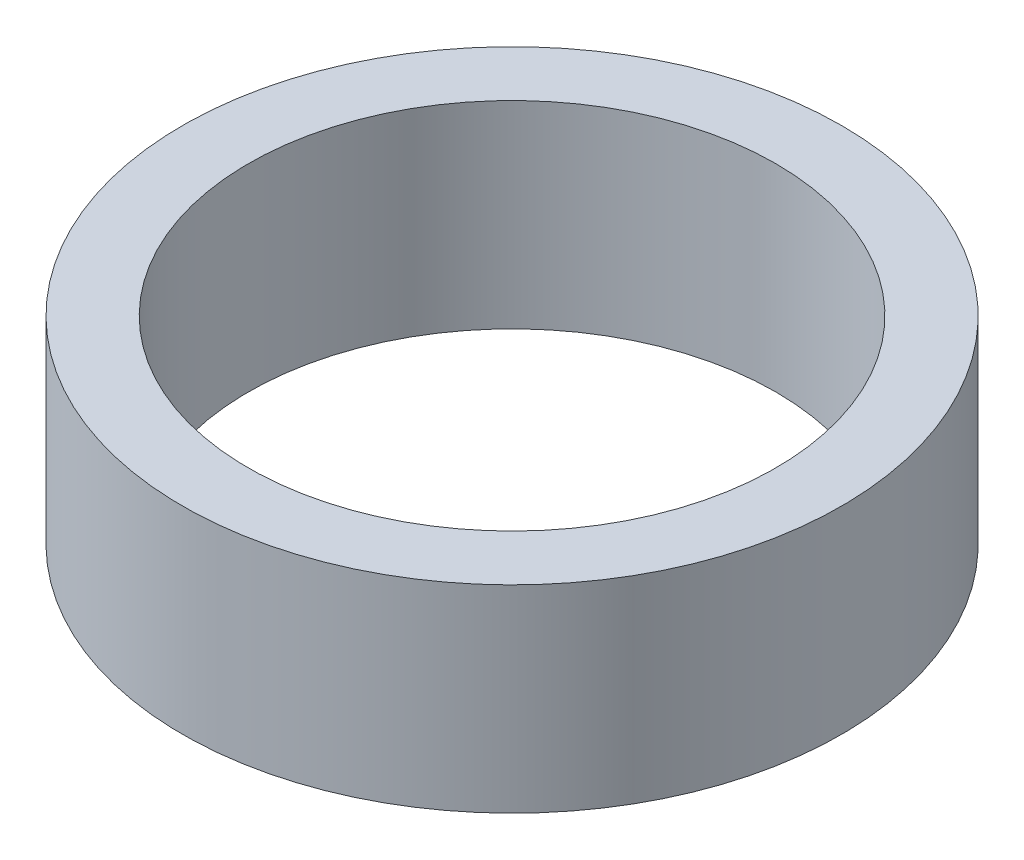
SolidWorks part; units mm, degrees
ref_plane "Front Plane" through (0, 0, 0) normal (0, 0, 1) x (1, 0, 0)
ref_plane "Top Plane" through (0, 0, 0) normal (0, 1, 0) x (1, 0, 0)
ref_plane "Right Plane" through (0, 0, 0) normal (1, 0, 0) x (0, 0, -1)
sketch "Sketch1" plane through (0, 0, 0) normal (0, 1, 0) x (1, 0, 0)
  circle A0 centre (0, 0) radius 12.7
  circle A1 centre (0, 0) radius 15.875
  dimension "D1" = 25.4
  dimension "D2" = 31.75
extrude "Boss-Extrude1" add sketch "Sketch1" along normal blind 9.525
